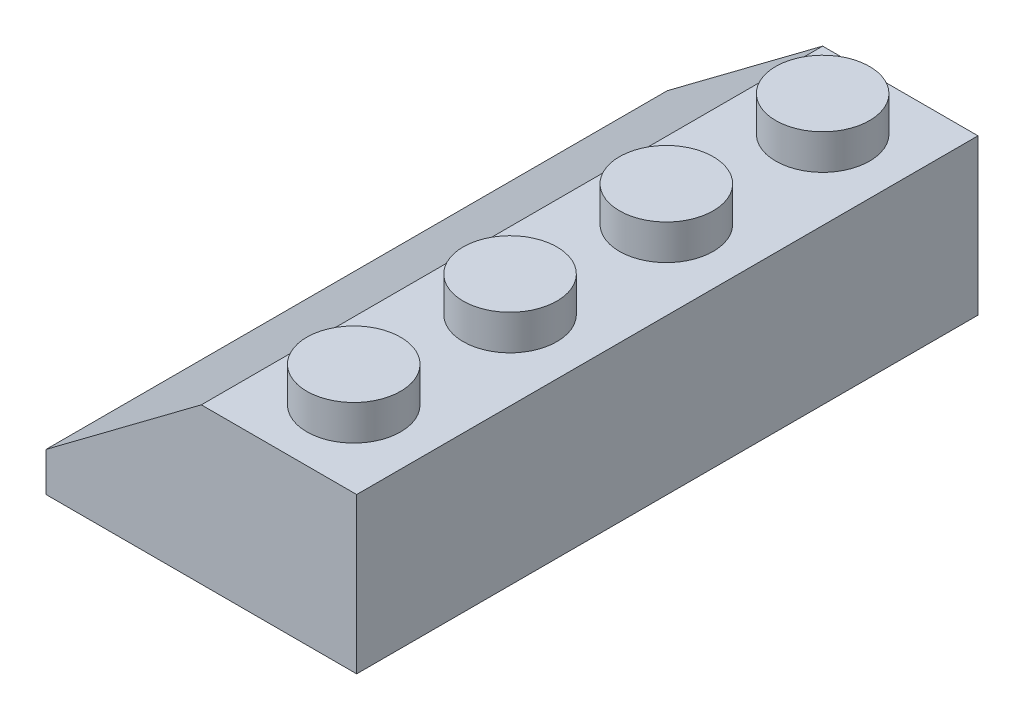
SolidWorks part; units mm, degrees
ref_plane "Front Plane" through (0, 0, 0) normal (0, 0, 1) x (1, 0, 0)
ref_plane "Top Plane" through (0, 0, 0) normal (0, 1, 0) x (1, 0, 0)
ref_plane "Right Plane" through (0, 0, 0) normal (1, 0, 0) x (0, 0, -1)
sketch "Sketch1" plane through (0, 0, 0) normal (0, 0, 1) x (1, 0, 0)
  line L0 (0, 0) -> (-15.9, 0)
  line L1 (-15.9, 0) -> (-15.9, 2)
  line L2 (-15.9, 2) -> (-7.95, 7.95)
  line L3 (-7.95, 7.95) -> (0, 7.95)
  line L4 (0, 7.95) -> (0, 0)
  point P3 (0, 0)
  point P7 (59.7702, 7.95)
  point P8 (0, 7.95)
  point P9 (-15.9, -43.5912)
  point P10 (-91.9863, 7.95)
  point P11 (-15.9, -19.4587)
  point P12 (-15.9, 0)
  point P13 (-15.9, 45.5135)
  point P14 (-15.9, 0)
  point P15 (0, 0)
  point P16 (0, 0)
  point P17 (-15.9, -13.8896)
  point P18 (-7.9865, 21.8451)
  point P19 (-15.9, 5.602)
  dimension "D1" = 15.9
  dimension "D2" = 7.95
  dimension "D3" = 2
  dimension "D4" = 7.95
extrude "Boss-Extrude1" add sketch "Sketch1" against normal mid plane 31.8
sketch "Sketch2" plane through (0, 7.95, 0) normal (0, 1, 0) x (1, 0, 0)
  line L0 (-7.95, 15.9) -> (-7.95, -15.9) construction
  line L1 (0, -15.9) -> (-7.95, -15.9) construction
  circle A0 centre (-4.05, -12) radius 2.4
  dimension "D1" = 4.8
  dimension "D2" = 3.9
  dimension "D3" = 3.9
extrude "Boss-Extrude2" add sketch "Sketch2" along normal blind 1.8
pattern_linear "LPattern1" count 4 spacing 8 along (0, 0, -1) of "Boss-Extrude2"
shell "Shell1" thickness 1.2
sketch "Sketch3" plane through (0, 6.75, 0) normal (0, -1, 0) x (1, 0, 0)
  line L0 (2.5332, 0) -> (-18.564, 0) construction
  line L1 (-4.05, -4) -> (-12.05, 4) construction
  line L2 (-12.05, 4) -> (-4.05, 4) construction
  line L3 (-4.05, 4) -> (-12.05, -4) construction
  line L4 (-12.05, -4) -> (-4.05, -4) construction
  circle A0 centre (-8.0154, 0) radius 3.25
  circle A1 centre (-8.0154, 0) radius 2.4
  dimension "D3" = 6.5
  dimension "D4" = 4.8
  dimension "D1" = 8
  dimension "D2" = 8
extrude "Boss-Extrude3" add sketch "Sketch3" along normal up to surface (6.75 mm away)
pattern_linear "LPattern3" count 2 spacing 8 along (0, 0, -1) count 2 spacing 8 along (0, 0, 1) of "Boss-Extrude3"
sketch "Sketch4" plane through (-6.6681, 8.9094, 0) normal (-0.5992, 0.8006, 0) x (0.8006, 0.5992, 0)
  line L4 (-11.5312, -15.9) -> (-1.6012, -15.9)
  line L5 (-1.6012, -15.9) -> (-1.6012, 15.9)
  line L6 (-1.6012, 15.9) -> (-11.5312, 15.9)
  line L7 (-11.5312, 15.9) -> (-11.5312, -15.9)
  line L8 (-11.5312, -15.9) -> (-1.6012, -15.9)
  line L9 (-1.6012, -15.9) -> (-1.6012, 15.9)
  line L10 (-1.6012, 15.9) -> (-11.5312, 15.9)
  line L11 (-11.5312, 15.9) -> (-11.5312, -15.9)
  dimension "D1" = 0
extrude "Cut-Extrude1" cut sketch "Sketch4" along normal through all
